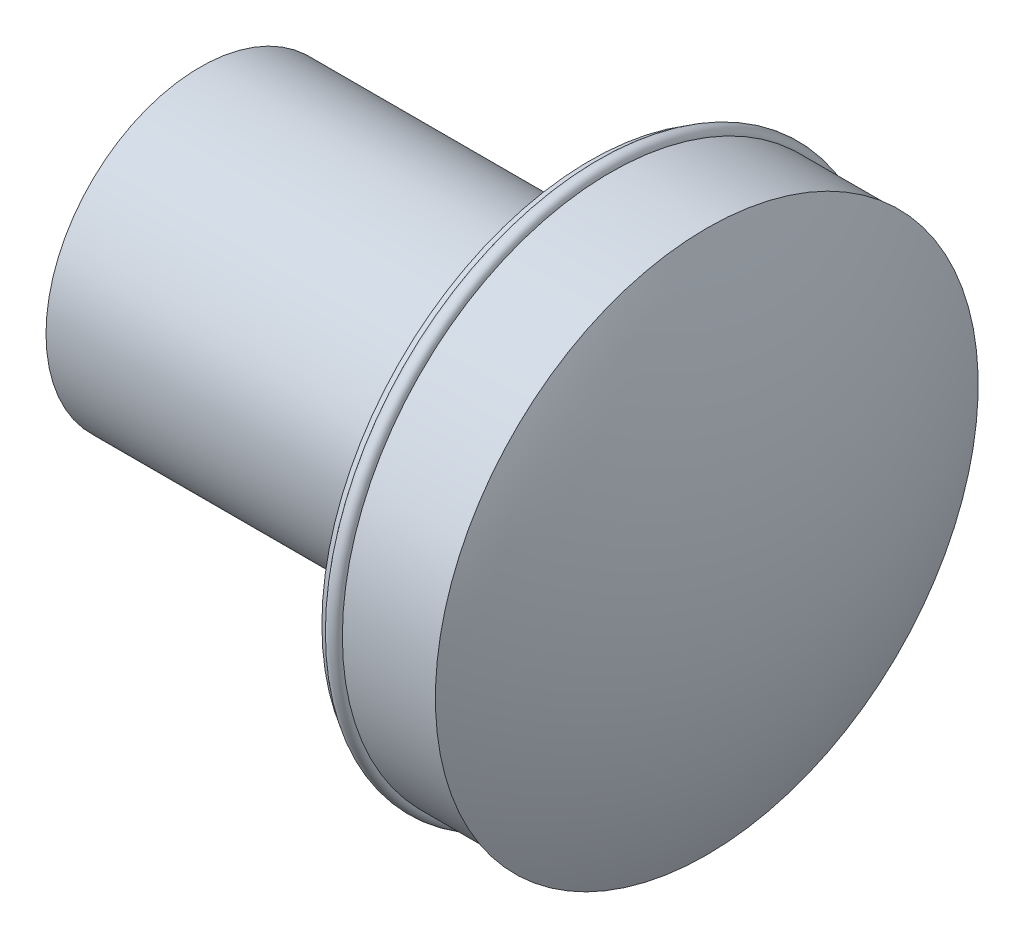
SolidWorks part; units mm, degrees
ref_plane "Front Plane" through (0, 0, 0) normal (0, 0, 1) x (1, 0, 0)
ref_plane "Top Plane" through (0, 0, 0) normal (0, 1, 0) x (1, 0, 0)
ref_plane "Right Plane" through (0, 0, 0) normal (1, 0, 0) x (0, 0, -1)
sketch "Sketch1" plane through (0, 0, 0) normal (0, 0, 1) x (1, 0, 0)
  line L0 (-76.8401, 0) -> (0, 0) construction
  line L1 (52.832, 0) -> (52.832, 27.94)
  line L2 (33.02, 16.0646) -> (40.64, 27.94)
  line L3 (40.64, 27.94) -> (41.3074, 27.94)
  line L4 (42.7742, 27.94) -> (52.832, 27.94)
  line L6 (33.02, 16.0646) -> (0, 16.0646)
  line L7 (0, 16.0646) -> (0, 0)
  line L8 (52.832, 0) -> (0, 0)
  arc A0 (41.3074, 27.94) -> (42.7742, 27.94) centre (42.0408, 27.94) cw
  dimension "D1" = 33.02
  dimension "D6" = 0.7334
  dimension "D2" = 7.62
  dimension "D3" = 12.192
  dimension "D4" = 27.94
  dimension "D5" = 57.313
  dimension "D7" = 16.0646
sketch "Sketch4" plane through (0, 0, 0) normal (0, 1, 0) x (1, 0, 0)
revolve "Revolve4" add sketch "Sketch1" angle 360 about L0
sketch "Sketch9" plane through (0, 0, 0) normal (0, 0, 1) x (1, 0, 0)
  line L0 (0, 0) -> (38.1, 0)
  dimension "D1" = 38.1
sketch "Sketch10" plane through (52.832, 0, 0) normal (1, 0, 0) x (0, 0, -1)
  circle A0 centre (0, 0) radius 28.2977
sketch "Sketch11" plane through (0, 0, 0) normal (0, 0, 1) x (1, 0, 0)
  line L0 (52.832, -0.3577) -> (59.182, -0.3577) construction
  line L1 (52.832, 27.94) -> (52.832, -0.3577)
  line L2 (52.832, -0.3577) -> (59.182, -0.3577)
  arc A0 (59.182, -0.3577) -> (52.832, 27.94) centre (-7.0451, -0.3577) ccw
  dimension "D2" = 66.2271
  dimension "D1" = 6.35
  dimension "D3" = 28.2977
revolve "Revolve7" add sketch "Sketch11" angle 360 about L0
